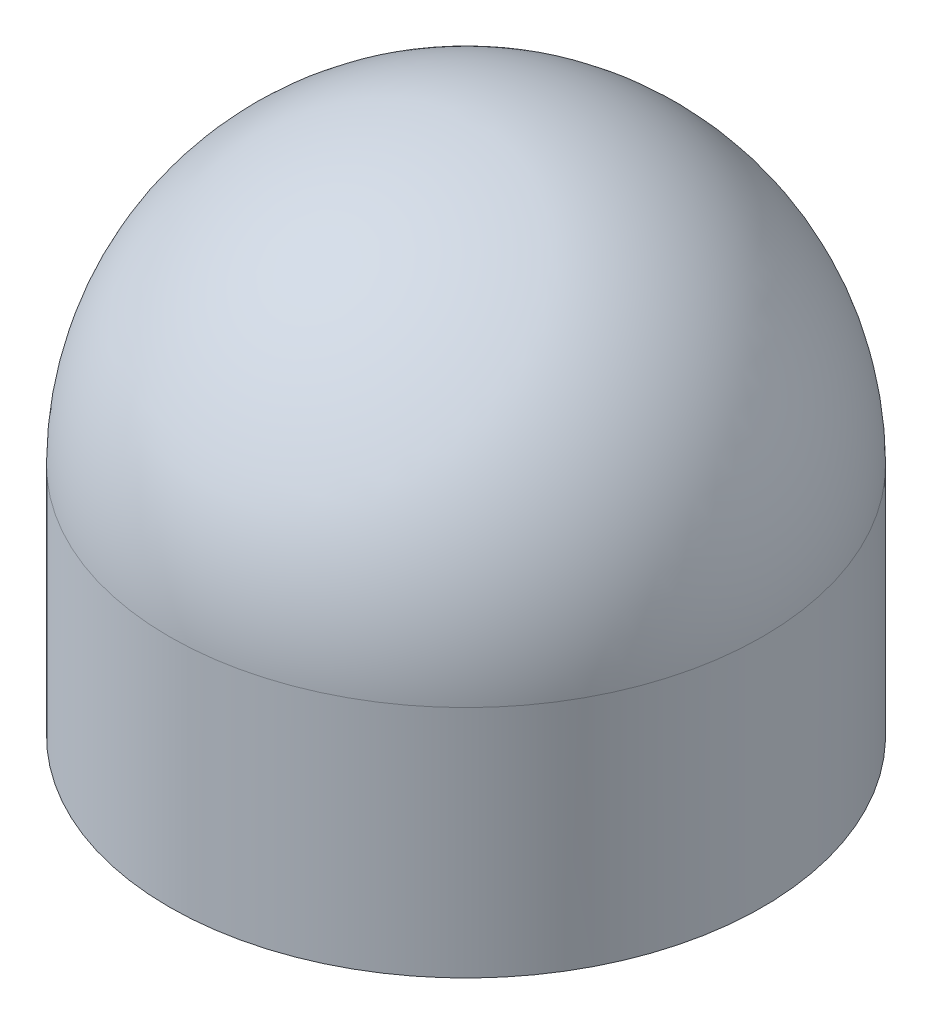
SolidWorks part; units mm, degrees
ref_plane "Front Plane" through (0, 0, 0) normal (0, 0, 1) x (1, 0, 0)
ref_plane "Top Plane" through (0, 0, 0) normal (0, 1, 0) x (1, 0, 0)
ref_plane "Right Plane" through (0, 0, 0) normal (1, 0, 0) x (0, 0, -1)
sketch "Sketch1" plane through (0, 0, 0) normal (0, 0, 1) x (1, 0, 0)
  line L0 (0, 17.272) -> (0, 7.62)
  line L1 (0, 0) -> (9.652, 0)
  line L2 (0, 0) -> (0, 7.62)
  line L4 (9.652, 0) -> (9.652, 7.62)
  arc A0 (9.652, 7.62) -> (0, 17.272) centre (0, 7.62) ccw
  dimension "D3" = 9.652
  dimension "D1" = 9.652
  dimension "D2" = 7.62
revolve "Revolve1" add sketch "Sketch1" angle 360 about L0
